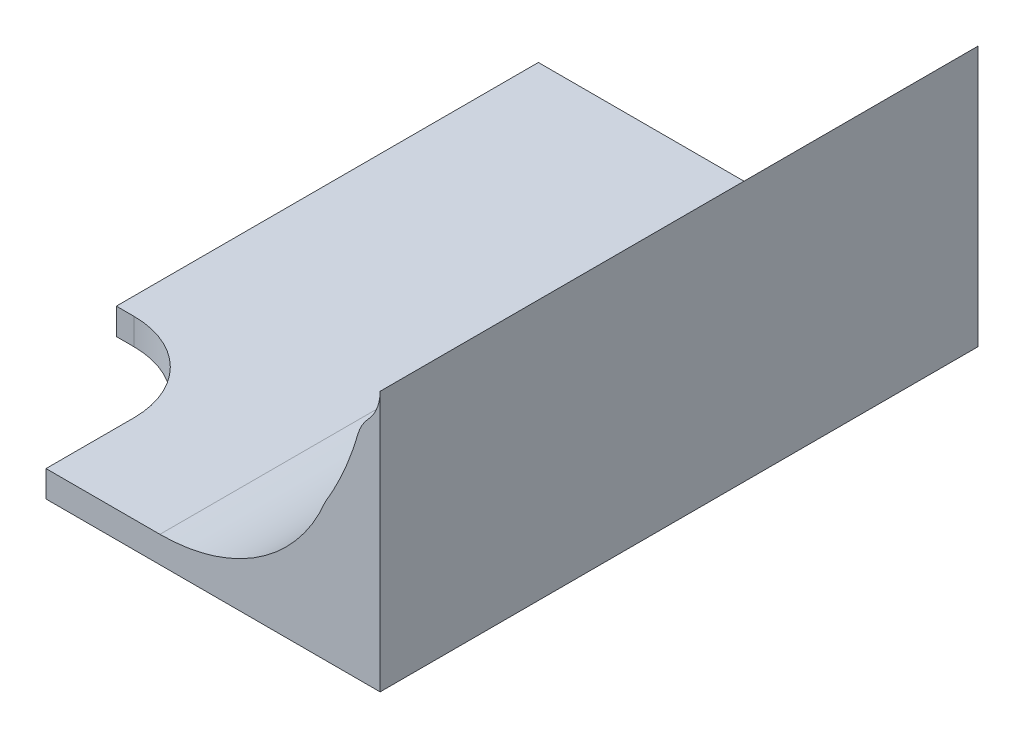
SolidWorks part; units mm, degrees
ref_plane "Front Plane" through (0, 0, 0) normal (0, 0, 1) x (1, 0, 0)
ref_plane "Top Plane" through (0, 0, 0) normal (0, 1, 0) x (1, 0, 0)
ref_plane "Right Plane" through (0, 0, 0) normal (1, 0, 0) x (0, 0, -1)
sketch "Sketch2" plane through (0, 0, 0) normal (0, 0, 1) x (1, 0, 0)
  line L0 (-46.6571, -11.6076) -> (-71.6133, -11.6076)
  line L1 (-71.6133, -11.6076) -> (-71.6133, -14.6073)
  line L2 (-71.6133, -14.6073) -> (-21.6133, -14.6073)
  line L3 (-21.6133, 15.0044) -> (-21.6133, -14.6073)
  arc A0 (-22.9706, 11.5794) -> (-21.6133, 15.0044) centre (-26.6133, 15.0044) ccw
  arc A1 (-22.9706, 11.5794) -> (-24.1335, 9.5352) centre (-19.328, 8.1543) ccw
  arc A2 (-27.8661, 0.9671) -> (-24.1335, 9.5352) centre (-58.5097, 19.4135) ccw
  arc A6 (-46.6571, -11.6076) -> (-27.8661, 0.9671) centre (-46.6571, 8.7199) ccw
  point P6 (-46.6133, -14.6073)
extrude "Boss-Extrude1" add sketch "Sketch2" along normal blind 68
sketch "Sketch3" plane through (0, -14.6073, 0) normal (0, -1, 0) x (-1, 0, 0)
  line L1 (71.6133, -68) -> (59.6133, -68)
  line L2 (71.6133, -68) -> (71.6133, -48)
  line L3 (71.6133, -48) -> (69.6133, -48)
  line L4 (59.6133, -68) -> (59.6133, -58)
  arc A0 (69.6133, -48) -> (59.6133, -58) centre (69.6133, -58) ccw
  dimension "D3" = 10
  dimension "D1" = 20
  dimension "D2" = 12
extrude "Cut-Extrude1" cut sketch "Sketch3" against normal blind 10 contours L2 L1 L4 A0 L3
